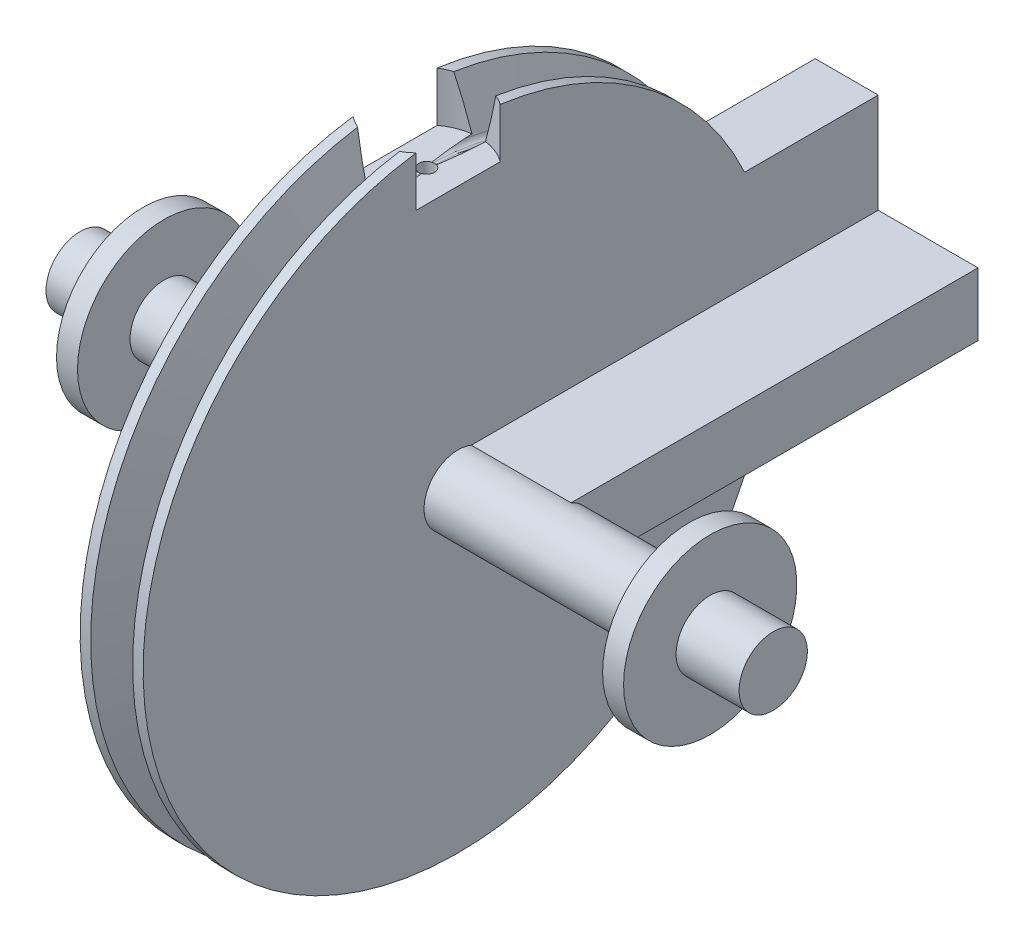
SolidWorks part; units mm, degrees
ref_plane "Front Plane" through (0, 0, 0) normal (0, 0, 1) x (1, 0, 0)
ref_plane "Top Plane" through (0, 0, 0) normal (0, 1, 0) x (1, 0, 0)
ref_plane "Right Plane" through (0, 0, 0) normal (1, 0, 0) x (0, 0, -1)
sketch "Sketch1" plane through (0, 0, 0) normal (0, 0, 1) x (1, 0, 0)
  line L0 (-33, 0) -> (33, 0)
  line L1 (-33, 0) -> (-33, 3.25)
  line L2 (-33, 3.25) -> (-27, 3.25)
  line L3 (33, 3.25) -> (33, 0)
  line L4 (-3, 3.25) -> (-3, 30)
  line L5 (-3, 30) -> (-2, 30)
  line L6 (3, 30) -> (3, 3.25)
  line L7 (0.5, 25) -> (-0.5, 25)
  line L8 (-27, 3.25) -> (-27, 8.25)
  line L9 (-27, 8.25) -> (-25, 8.25)
  line L10 (-25, 8.25) -> (-25, 3.25)
  line L11 (25, 3.25) -> (25, 8.25)
  line L12 (25, 8.25) -> (27, 8.25)
  line L13 (27, 8.25) -> (27, 3.25)
  line L14 (-25, 3.25) -> (-3, 3.25)
  line L15 (27, 3.25) -> (33, 3.25)
  line L16 (3, 3.25) -> (25, 3.25)
  line L17 (-2, 30) -> (-0.5, 25)
  line L19 (2, 30) -> (3, 30)
  line L20 (0.5, 25) -> (2, 30)
  dimension "D1" = 33
  dimension "D2" = 33
  dimension "D3" = 3.25
  dimension "D4" = 22
  dimension "D5" = 22
  dimension "D6" = 2
  dimension "D7" = 5
  dimension "D8" = 2
  dimension "D9" = 5
  dimension "D10" = 1
  dimension "D11" = 1
  dimension "D12" = 1
  dimension "D13" = 2.5
  dimension "D14" = 5
  dimension "D15" = 26.75
revolve "Revolve1" add sketch "Sketch1" angle 360 about L0
fillet "Fillet3" radius 0.5 2 edges at (0.5, 0, 25) (-0.5, 0, 25)
sketch "Sketch2" plane through (0, 0, 0) normal (1, 0, 0) x (0, 0, -1)
  line L0 (0, 0) -> (47.727, 0) construction
  line L1 (0, 12.5) -> (40, 12.5)
  line L2 (0, 12.5) -> (0, -12.5)
  line L3 (0, -12.5) -> (40, -12.5)
  line L4 (40, 12.5) -> (40, -12.5)
  line L5 (0, 6.278) -> (0, -9.473) construction
  dimension "D1" = 40
  dimension "D2" = 12.5
  dimension "D3" = 12.5
extrude "Boss-Extrude1" add sketch "Sketch2" along normal blind 3 and the other way blind 3
sketch "Sketch3" plane through (0, 0, 0) normal (0, 1, 0) x (1, 0, 0)
  line L1 (-12.5, 0) -> (12.5, 0)
  line L2 (-12.5, 0) -> (-12.5, 40)
  line L3 (-12.5, 40) -> (12.5, 40)
  line L4 (12.5, 0) -> (12.5, 40)
  dimension "D1" = 40
  dimension "D2" = 12.5
  dimension "D3" = 12.5
extrude "Boss-Extrude2" add sketch "Sketch3" along normal blind 3 and the other way blind 3
sketch "Sketch4" plane through (0, 0, -40) normal (0, 0, -1) x (-1, 0, 0)
  line L0 (0, -4.5322) -> (0, 5.501) construction
  line L1 (-3.7019, 0) -> (3.2176, 0) construction
  circle A0 centre (7, 0) radius 0.5
  circle A1 centre (-7, 0) radius 0.5
  circle A2 centre (0, 7) radius 0.5
  circle A3 centre (0, -7) radius 0.5
  dimension "D1" = 1
  dimension "D3" = 1
  dimension "D5" = 1
  dimension "D7" = 1
  dimension "D2" = 7
  dimension "D4" = 7
  dimension "D6" = 7
  dimension "D8" = 7
extrude "Cut-Extrude1" cut sketch "Sketch4" against normal blind 3
ref_plane "Plane1" through (0, 25, 0) normal (0, 1, 0) x (1, 0, 0)
sketch "Sketch5" plane through (0, 25, 0) normal (0, 1, 0) x (1, 0, 0)
  line L0 (-1.3965, 0) -> (1.4841, 0) construction
  line L1 (0, 0.819) -> (0, -0.7836) construction
  circle A0 centre (0, 0) radius 0.75
  dimension "D1" = 1.5
extrude "Cut-Extrude2" cut sketch "Sketch5" against normal blind 10
sketch "Sketch6" plane through (0, 25, 0) normal (0, 1, 0) x (1, 0, 0)
  circle A0 centre (0, 0) radius 5
  dimension "D1" = 10
extrude "Cut-Extrude3" cut sketch "Sketch6" along normal through all
